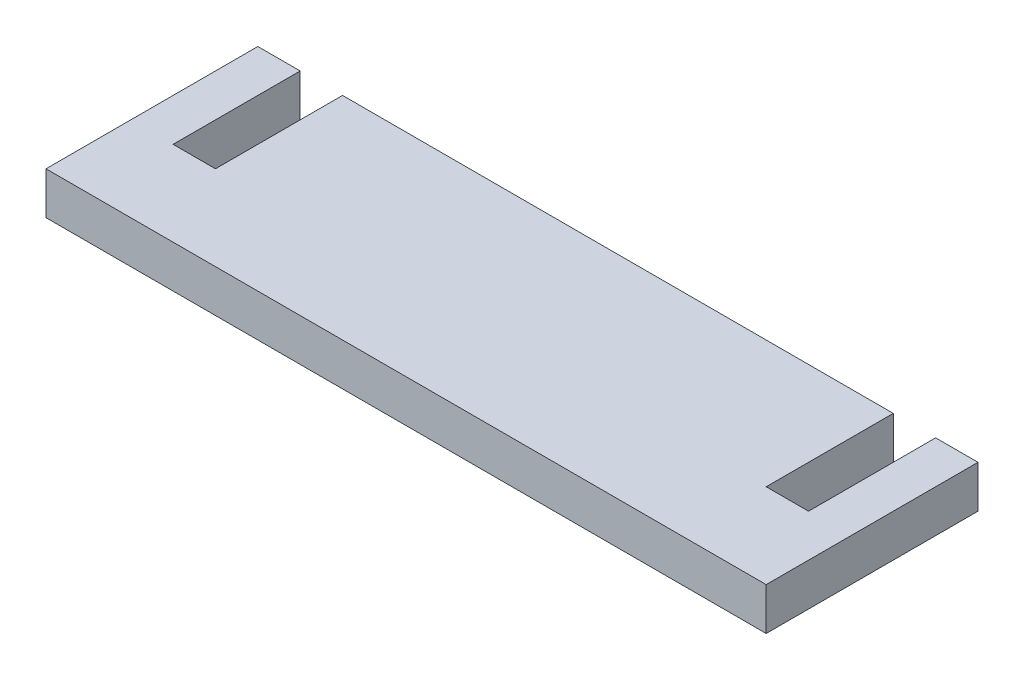
SolidWorks part; units mm, degrees
ref_plane "Front Plane" through (0, 0, 0) normal (0, 0, 1) x (1, 0, 0)
ref_plane "Top Plane" through (0, 0, 0) normal (0, 1, 0) x (1, 0, 0)
ref_plane "Right Plane" through (0, 0, 0) normal (1, 0, 0) x (0, 0, -1)
sketch "Sketch1" plane through (0, 0, 0) normal (0, 1, 0) x (1, 0, 0)
  line L0 (0, 0) -> (-4318, 0)
  line L1 (-4318, 1270) -> (-4064, 1270)
  line L2 (-4064, 1270) -> (-4064, 508)
  line L3 (-4064, 508) -> (-3810, 508)
  line L4 (-3810, 508) -> (-3810, 1270)
  line L5 (-3810, 1270) -> (-508, 1270)
  line L6 (-508, 1270) -> (-508, 508)
  line L7 (-508, 508) -> (-254, 508)
  line L8 (-254, 508) -> (-254, 1270)
  line L9 (-254, 1270) -> (0, 1270)
  line L10 (0, 1270) -> (0, 0)
  line L12 (-4318, 1270) -> (-4318, 0)
  dimension "D1" = 4318
  dimension "D2" = 1270
  dimension "D3" = 254
  dimension "D4" = 254
  dimension "D5" = 254
  dimension "D6" = 762
  dimension "D7" = 762
  dimension "D8" = 762
  dimension "D9" = 762
  dimension "D10" = 254
extrude "Boss-Extrude1" add sketch "Sketch1" along normal blind 254
